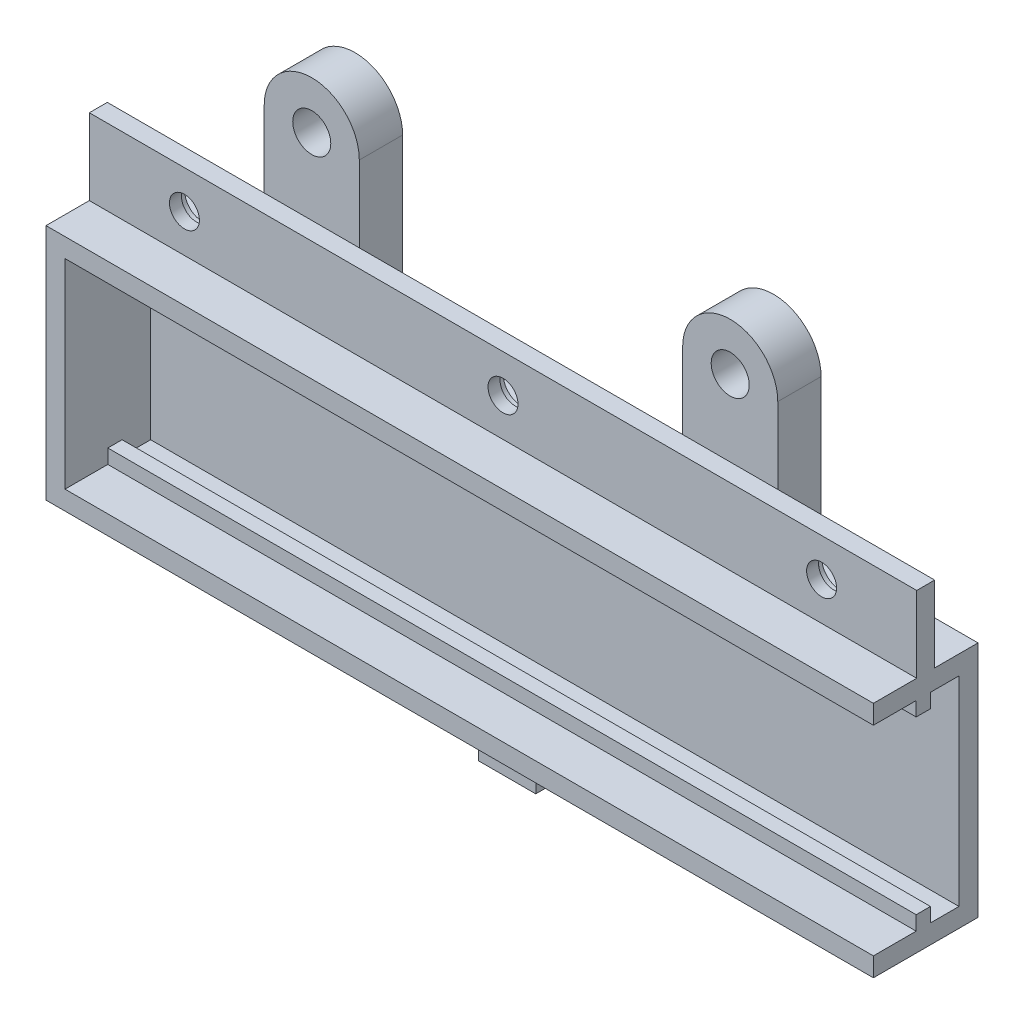
SolidWorks part; units mm, degrees
ref_plane "Front Plane" through (0, 0, 0) normal (0, 0, 1) x (1, 0, 0)
ref_plane "Top Plane" through (0, 0, 0) normal (0, 1, 0) x (1, 0, 0)
ref_plane "Right Plane" through (0, 0, 0) normal (1, 0, 0) x (0, 0, -1)
sketch "Sketch1" plane through (0, 0, 0) normal (0, 0, 1) x (1, 0, 0)
  line L0 (-65.8813, 16.6687) -> (65.8812, 16.6687)
  line L1 (-65.0875, -15.875) -> (65.0875, -15.875) construction
  line L2 (-65.0875, -15.875) -> (-65.0875, 15.875) construction
  line L3 (-65.0875, 15.875) -> (65.0875, 15.875) construction
  line L4 (65.0875, -15.875) -> (65.0875, 15.875) construction
  line L5 (-65.0875, -15.875) -> (65.0875, 15.875) construction
  line L6 (-65.0875, 15.875) -> (65.0875, -15.875) construction
  line L7 (65.8812, -16.6688) -> (65.8812, 16.6687)
  line L8 (-65.8813, -16.6688) -> (65.8812, -16.6688)
  line L9 (-65.8813, -16.6688) -> (-65.8813, 16.6687)
  line L10 (-69.0563, 19.8437) -> (69.0562, 19.8438)
  line L11 (69.0562, -19.8438) -> (69.0562, 19.8438)
  line L12 (-69.0563, -19.8438) -> (69.0562, -19.8438)
  line L13 (-69.0563, -19.8438) -> (-69.0563, 19.8437)
  point P0 (0, 0)
  dimension "D1" = 130.175
  dimension "D2" = 31.75
  dimension "D3" = 0.7937
  dimension "D4" = 3.175
extrude "Boss-Extrude1" add sketch "Sketch1" along normal blind 14.2875
sketch "Sketch2" plane through (0, 0, 0) normal (0, 0, -1) x (-1, 0, 0)
  line L4 (69.0563, -19.8438) -> (69.0563, 19.8437)
  line L5 (69.0563, 19.8437) -> (-69.0562, 19.8438)
  line L6 (-69.0562, 19.8438) -> (-69.0562, -19.8438)
  line L7 (-69.0562, -19.8438) -> (69.0563, -19.8438)
  line L8 (69.0563, -19.8438) -> (69.0563, 19.8437)
  line L9 (69.0563, 19.8437) -> (-69.0562, 19.8438)
  line L10 (-69.0562, 19.8438) -> (-69.0562, -19.8438)
  line L11 (-69.0562, -19.8438) -> (69.0563, -19.8438)
  dimension "D1" = 0
extrude "Boss-Extrude2" add sketch "Sketch2" along normal blind 3.175
sketch "Sketch3" plane through (69.0562, 0, 0) normal (1, 0, 0) x (0, 0, -1)
  line L4 (0, -16.6687) -> (0, 16.6688)
  line L5 (0, 16.6688) -> (-14.2875, 16.6688)
  line L6 (-14.2875, 16.6688) -> (-14.2875, -16.6687)
  line L7 (-14.2875, -16.6687) -> (0, -16.6687)
  line L8 (0, -16.6687) -> (0, 16.6688)
  line L9 (0, 16.6688) -> (-14.2875, 16.6688)
  line L10 (-14.2875, 16.6688) -> (-14.2875, -16.6687)
  line L11 (-14.2875, -16.6687) -> (0, -16.6687)
  dimension "D1" = 0
extrude "Cut-Extrude1" cut sketch "Sketch3" against normal up to next
sketch "Sketch4" plane through (69.0562, 0, 0) normal (1, 0, 0) x (0, 0, -1)
  line L0 (-14.2875, -16.6687) -> (0, -16.6687) construction
  line L1 (-7.1437, -16.6687) -> (-4.7625, -16.6687)
  line L2 (-7.1437, -16.6687) -> (-7.1437, -14.2875)
  line L3 (-7.1437, -14.2875) -> (-4.7625, -14.2875)
  line L4 (-4.7625, -16.6687) -> (-4.7625, -14.2875)
  line L5 (0, 16.6688) -> (-14.2875, 16.6688) construction
  line L6 (-7.1437, 16.6688) -> (-4.7625, 16.6688)
  line L7 (-7.1437, 16.6688) -> (-7.1437, 14.2875)
  line L8 (-7.1437, 14.2875) -> (-4.7625, 14.2875)
  line L9 (-4.7625, 16.6688) -> (-4.7625, 14.2875)
  line L10 (-14.2875, -19.8438) -> (-14.2875, -16.6687) construction
  dimension "D1" = 7.1437
  dimension "D2" = 2.3812
  dimension "D3" = 2.3812
extrude "Boss-Extrude3" add sketch "Sketch4" against normal up to next
sketch "Sketch6" plane through (0, 0, -3.175) normal (0, 0, -1) x (-1, 0, 0)
  line L0 (69.0563, -19.8438) -> (69.0563, 19.8437) construction
  line L1 (-69.0562, 19.8438) -> (69.0563, 19.8438)
  line L2 (-69.0562, 19.8438) -> (-69.0562, 32.5437)
  line L3 (-69.0562, 32.5437) -> (69.0563, 32.5437)
  line L4 (69.0563, 19.8438) -> (69.0563, 32.5437)
  line L5 (-53.1812, 26.1937) -> (0, 26.1937) construction
  line L6 (0, 26.1937) -> (53.1812, 26.1937) construction
  circle A0 centre (0, 26.1937) radius 2.5
  circle A1 centre (-53.1812, 26.1937) radius 2.5
  circle A2 centre (53.1812, 26.1937) radius 2.5
  point P13 (51.3773, 26.1937)
  point P14 (-69.0562, 26.1937)
  dimension "D2" = 5
  dimension "D1" = 12.7
  dimension "D3" = 15.875
extrude "Boss-Extrude4" add sketch "Sketch6" along normal mid plane 3 from offset 8.7312 offset against normal yes
sketch "Sketch7" plane through (0, 0, 4.0563) normal (0, 0, -1) x (-1, 0, 0)
  circle A0 centre (-53.1812, 26.1937) radius 2.95
  circle A1 centre (0, 26.1937) radius 2.95
  circle A2 centre (53.1812, 26.1937) radius 2.95
  dimension "D1" = 5.9
extrude "Cut-Extrude2" cut sketch "Sketch7" against normal blind 1
sketch "Sketch8" plane through (0, -19.8438, 0) normal (0, -1, 0) x (1, 0, 0)
  line L0 (69.0562, -3.175) -> (-69.0563, -3.175) construction
  line L1 (-4.7625, 6.35) -> (4.7625, 6.35)
  line L2 (-4.7625, 6.35) -> (-4.7625, -3.175)
  line L3 (-4.7625, -3.175) -> (4.7625, -3.175)
  line L4 (4.7625, 6.35) -> (4.7625, -3.175)
  line L5 (-4.7625, 6.35) -> (4.7625, -3.175) construction
  line L6 (-4.7625, -3.175) -> (4.7625, 6.35) construction
  point P0 (0, 1.5875)
  point P7 (0, 0)
  point P8 (-17.06, 1.5875)
  point P10 (0, -3.175)
  dimension "D1" = 9.525
  dimension "D2" = 9.525
extrude "Boss-Extrude5" add sketch "Sketch8" along normal blind 9.525
sketch "Sketch9" plane through (0, 0, 7.0563) normal (0, 0, 1) x (1, 0, 0)
  line L0 (69.0562, 32.5437) -> (69.0562, 19.8438) construction
  line L1 (-69.0563, 19.8437) -> (69.0562, 19.8437)
  line L2 (-69.0563, 19.8437) -> (-69.0563, 57.9437)
  line L3 (-69.0563, 57.9437) -> (69.0562, 57.9437)
  line L4 (69.0562, 19.8437) -> (69.0562, 57.9437)
  line L5 (-69.0563, 32.5437) -> (69.0562, 32.5437) construction
  line L8 (42.8625, 45.2437) -> (42.8625, 19.8437)
  line L9 (42.8625, 19.8437) -> (26.9875, 19.8437)
  line L10 (26.9875, 45.2437) -> (26.9875, 19.8437)
  line L12 (-26.9875, 45.2437) -> (-26.9875, 19.8437)
  line L13 (-26.9875, 19.8437) -> (-42.8625, 19.8437)
  line L14 (-42.8625, 45.2437) -> (-42.8625, 19.8437)
  circle A0 centre (-34.925, 45.2437) radius 3.175
  circle A1 centre (34.925, 45.2437) radius 3.175
  circle A2 centre (-53.1812, 26.1937) radius 2.95 construction
  circle A3 centre (0, 26.1937) radius 2.95 construction
  circle A4 centre (53.1812, 26.1937) radius 2.95 construction
  circle A5 centre (-53.1812, 26.1937) radius 2.95
  circle A6 centre (0, 26.1937) radius 2.95
  circle A7 centre (53.1812, 26.1937) radius 2.95
  arc A8 (42.8625, 45.2437) -> (26.9875, 45.2437) centre (34.925, 45.2437) ccw
  arc A9 (-26.9875, 45.2437) -> (-42.8625, 45.2437) centre (-34.925, 45.2437) ccw
  circle A10 centre (-34.925, 45.2437) radius 7.9375 construction
  circle A11 centre (34.925, 45.2437) radius 7.9375 construction
  point P14 (0, 19.8437)
  line M9 (69.0562, 32.5437) -> (-69.0563, 32.5437)
  dimension "D5" = 6.35
  dimension "D1" = 25.4
  dimension "D2" = 12.7
  dimension "D3" = 69.85
  dimension "D4" = 34.925
  dimension "D6" = 4.7625
extrude "Boss-Extrude6" add sketch "Sketch9" along normal up to surface (7.2313 mm away) from surface at -10.2312 contours L14 L1 L12 M9 | L12 A9 L14 A0 M9 | L10 L1 L8 M9 | L8 A8 L10 A1 M9 up to face at (50.2312, 26.1937, 4.0563) starting at face at (0, -12.3031, -3.175)
